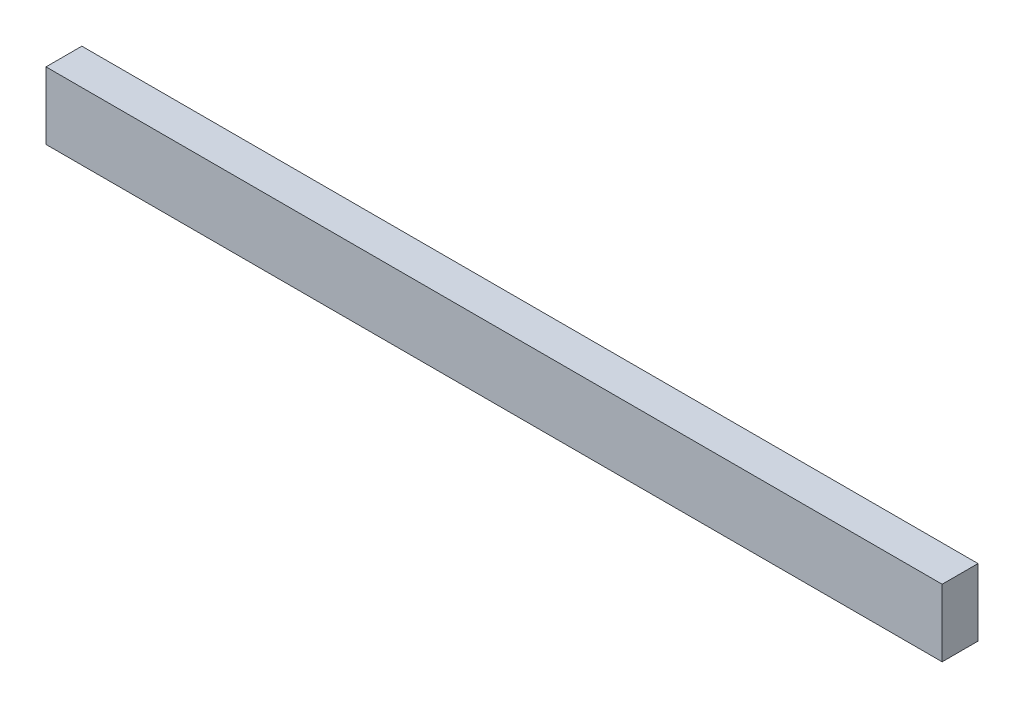
SolidWorks part; units mm, degrees
ref_plane "Front Plane" through (0, 0, 0) normal (0, 0, 1) x (1, 0, 0)
ref_plane "Top Plane" through (0, 0, 0) normal (0, 1, 0) x (1, 0, 0)
ref_plane "Right Plane" through (0, 0, 0) normal (1, 0, 0) x (0, 0, -1)
sketch "Sketch1" plane through (0, 0, 0) normal (0, 0, 1) x (1, 0, 0)
  line L1 (-125, 9.375) -> (125, 9.375)
  line L2 (-125, 9.375) -> (-125, -9.375)
  line L3 (-125, -9.375) -> (125, -9.375)
  line L4 (125, 9.375) -> (125, -9.375)
  line L5 (-125, 9.375) -> (125, -9.375) construction
  line L6 (-125, -9.375) -> (125, 9.375) construction
  point P0 (0, 0)
  dimension "D1" = 250
  dimension "D2" = 18.75
extrude "Boss-Extrude1" add sketch "Sketch1" along normal blind 10
